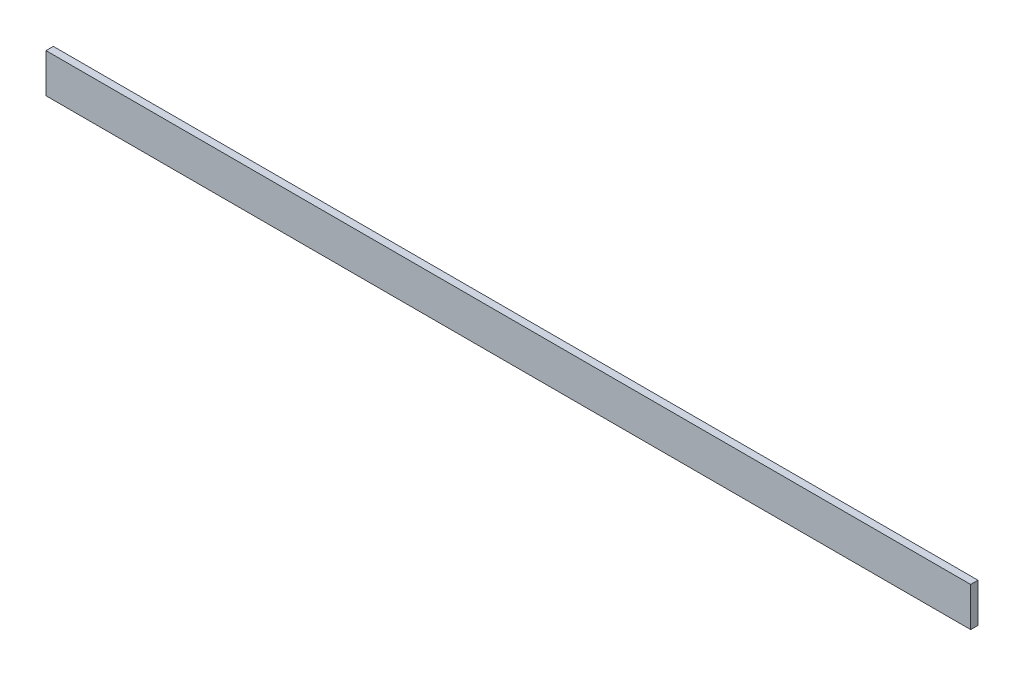
SolidWorks part; units mm, degrees
ref_plane "Front Plane" through (0, 0, 0) normal (0, 0, 1) x (1, 0, 0)
ref_plane "Top Plane" through (0, 0, 0) normal (0, 1, 0) x (1, 0, 0)
ref_plane "Right Plane" through (0, 0, 0) normal (1, 0, 0) x (0, 0, -1)
sketch "Sketch2" plane through (0, 0, 0) normal (0, 0, 1) x (1, 0, 0)
  line L1 (-1200.15, -50.8) -> (1200.15, -50.8)
  line L2 (-1200.15, -50.8) -> (-1200.15, 50.8)
  line L3 (-1200.15, 50.8) -> (1200.15, 50.8)
  line L4 (1200.15, -50.8) -> (1200.15, 50.8)
  line L5 (-1200.15, -50.8) -> (1200.15, 50.8) construction
  line L6 (-1200.15, 50.8) -> (1200.15, -50.8) construction
  point P0 (0, 0)
  dimension "D1" = 2400.3
  dimension "D2" = 101.6
extrude "Boss-Extrude1" add sketch "Sketch2" along normal blind 19.05
